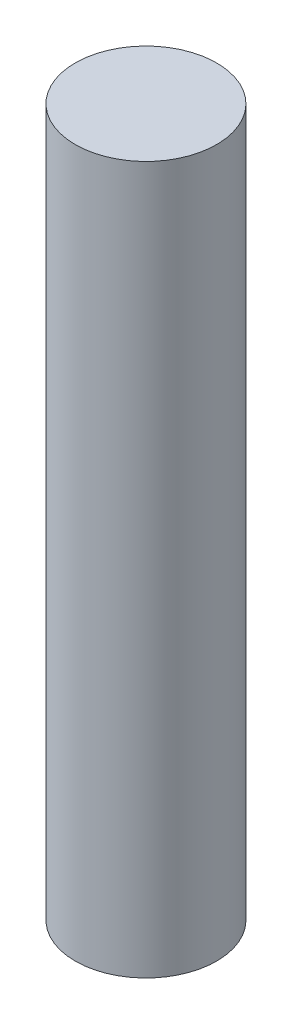
SolidWorks part; units mm, degrees
material "ABS"
ref_plane "Front Plane" through (0, 0, 0) normal (0, 0, 1) x (1, 0, 0)
ref_plane "Top Plane" through (0, 0, 0) normal (0, 1, 0) x (1, 0, 0)
ref_plane "Right Plane" through (0, 0, 0) normal (1, 0, 0) x (0, 0, -1)
sketch "Sketch1" plane through (0, 0, 0) normal (0, 1, 0) x (1, 0, 0)
  circle A0 centre (0, 0) radius 2.54
  point P3 (2.54, 0)
  point P4 (0, 2.54)
  point P5 (-2.54, 0)
  point P6 (0, -2.54)
  dimension "D1" = 5.08
extrude "Boss-Extrude1" add sketch "Sketch1" along normal blind 25.4
sketch "Sketch2" plane through (0, 25.4, 0) normal (0, 1, 0) x (1, 0, 0)
  circle A0 centre (0, 0) radius 2.54 construction
  point P0 (-2.54, 0)
  point P1 (0, 2.54)
  point P4 (-2.54, 0)
  point P5 (0, -2.54)
